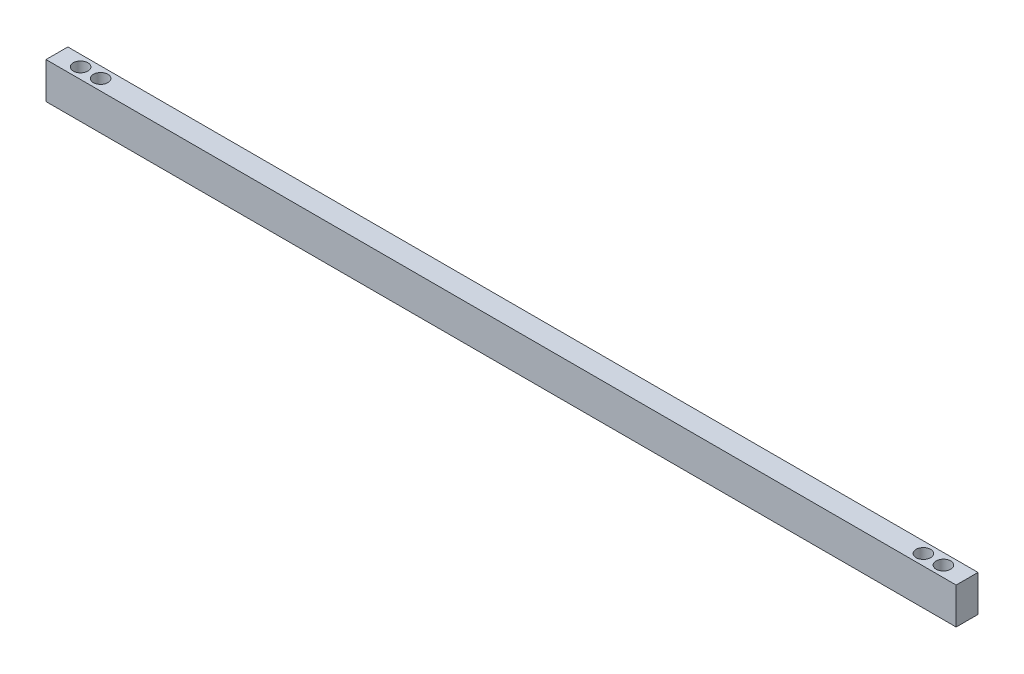
SolidWorks part; units mm, degrees
ref_plane "Front Plane" through (0, 0, 0) normal (0, 0, 1) x (1, 0, 0)
ref_plane "Top Plane" through (0, 0, 0) normal (0, 1, 0) x (1, 0, 0)
ref_plane "Right Plane" through (0, 0, 0) normal (1, 0, 0) x (0, 0, -1)
sketch "Sketch1" plane through (0, 0, 0) normal (0, 1, 0) x (1, 0, 0)
  line L1 (-317.5, -7.62) -> (317.5, -7.62)
  line L2 (-317.5, -7.62) -> (-317.5, 7.62)
  line L3 (-317.5, 7.62) -> (317.5, 7.62)
  line L4 (317.5, -7.62) -> (317.5, 7.62)
  line L5 (-317.5, -7.62) -> (317.5, 7.62) construction
  line L6 (-317.5, 7.62) -> (317.5, -7.62) construction
  point P0 (0, 0)
  dimension "D1" = 635
extrude "Boss-Extrude1" add sketch "Sketch1" along normal blind 25.4
sketch "Sketch2" plane through (0, 25.4, 0) normal (0, 1, 0) x (1, 0, 0)
  circle A0 centre (-300.99, 0) radius 5.08
  circle A1 centre (-287.02, 0) radius 5.08
  circle A2 centre (300.99, 0) radius 5.08
  circle A3 centre (287.02, 0) radius 5.08
extrude "Cut-Extrude1" cut sketch "Sketch2" against normal blind 27.94
